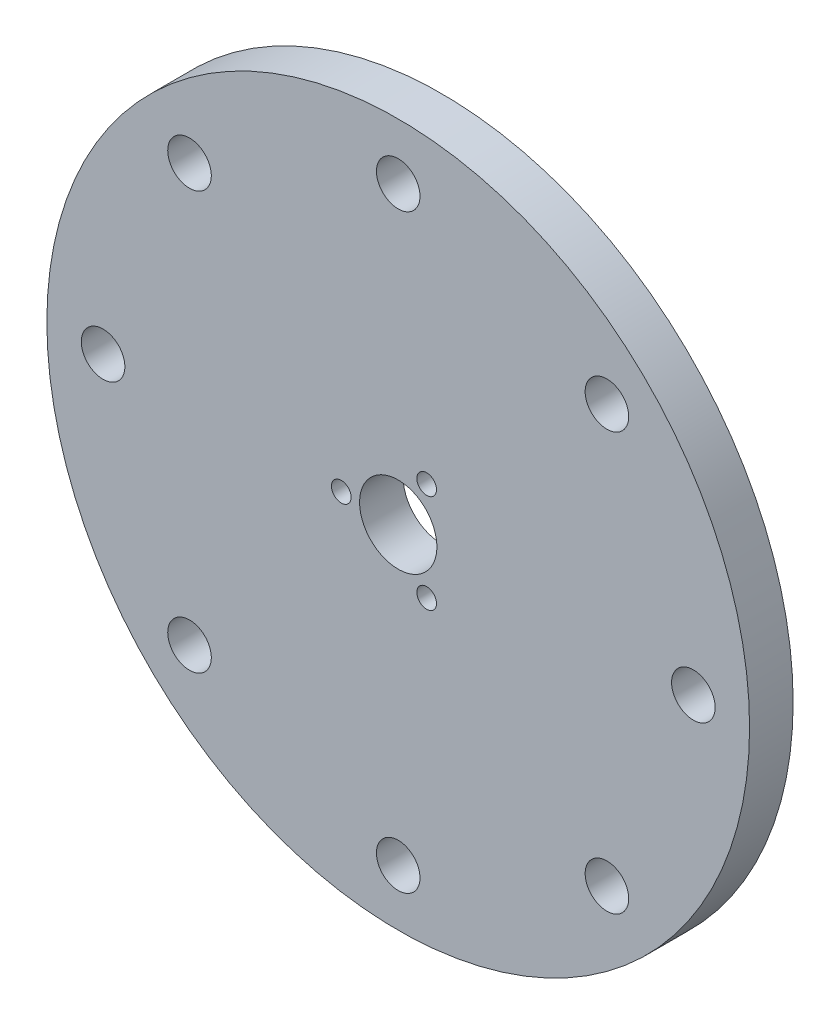
SolidWorks part; units mm, degrees
ref_plane "Front Plane" through (0, 0, 0) normal (0, 0, 1) x (1, 0, 0)
ref_plane "Top Plane" through (0, 0, 0) normal (0, 1, 0) x (1, 0, 0)
ref_plane "Right Plane" through (0, 0, 0) normal (1, 0, 0) x (0, 0, -1)
sketch "Sketch1" plane through (0, 0, 0) normal (0, 0, 1) x (1, 0, 0)
  circle A0 centre (0, 0) radius 50
  dimension "D1" = 100
extrude "Boss-Extrude1" add sketch "Sketch1" along normal blind 6.2
sketch "Sketch2" plane through (0, 0, 0) normal (0, 0, -1) x (-1, 0, 0)
  circle A0 centre (0, 0) radius 5.5
  dimension "D1" = 11
extrude "Cut-Extrude1" cut sketch "Sketch2" against normal through all
sketch "Sketch3" plane through (0, 0, 0) normal (0, 0, -1) x (-1, 0, 0)
  line L0 (-5.5, 0) -> (12.8933, 0) construction
  circle A0 centre (0, 0) radius 5.5 construction
  circle A1 centre (8.1, 0) radius 1.4
  circle A2 centre (-4.05, -7.0148) radius 1.4
  circle A3 centre (-4.05, 7.0148) radius 1.4
  dimension "D1" = 2.8
  dimension "D2" = 13.6
  dimension "D3" = 3
extrude "Cut-Extrude2" cut sketch "Sketch3" against normal through all
sketch "Sketch4" plane through (0, 0, 0) normal (0, 0, -1) x (-1, 0, 0)
  line L0 (50, 0) -> (-50, 0) construction
  circle A3 centre (0, 0) radius 50 construction
  circle A4 centre (42, 0) radius 3.1
  circle A5 centre (29.6985, -29.6985) radius 3.1
  circle A6 centre (0, -42) radius 3.1
  circle A7 centre (-29.6985, -29.6985) radius 3.1
  circle A8 centre (-42, 0) radius 3.1
  circle A9 centre (-29.6985, 29.6985) radius 3.1
  circle A10 centre (0, 42) radius 3.1
  circle A11 centre (29.6985, 29.6985) radius 3.1
  dimension "D1" = 6.2
  dimension "D3" = 8
  dimension "D2" = 8
extrude "Cut-Extrude3" cut sketch "Sketch4" against normal through all
equation "\"acrylic\"=6.2"
equation "\"D1@Boss-Extrude1\"=\"acrylic\""
equation "\"diam\"=100"
equation "\"D1@Sketch1\"=\"diam\""
